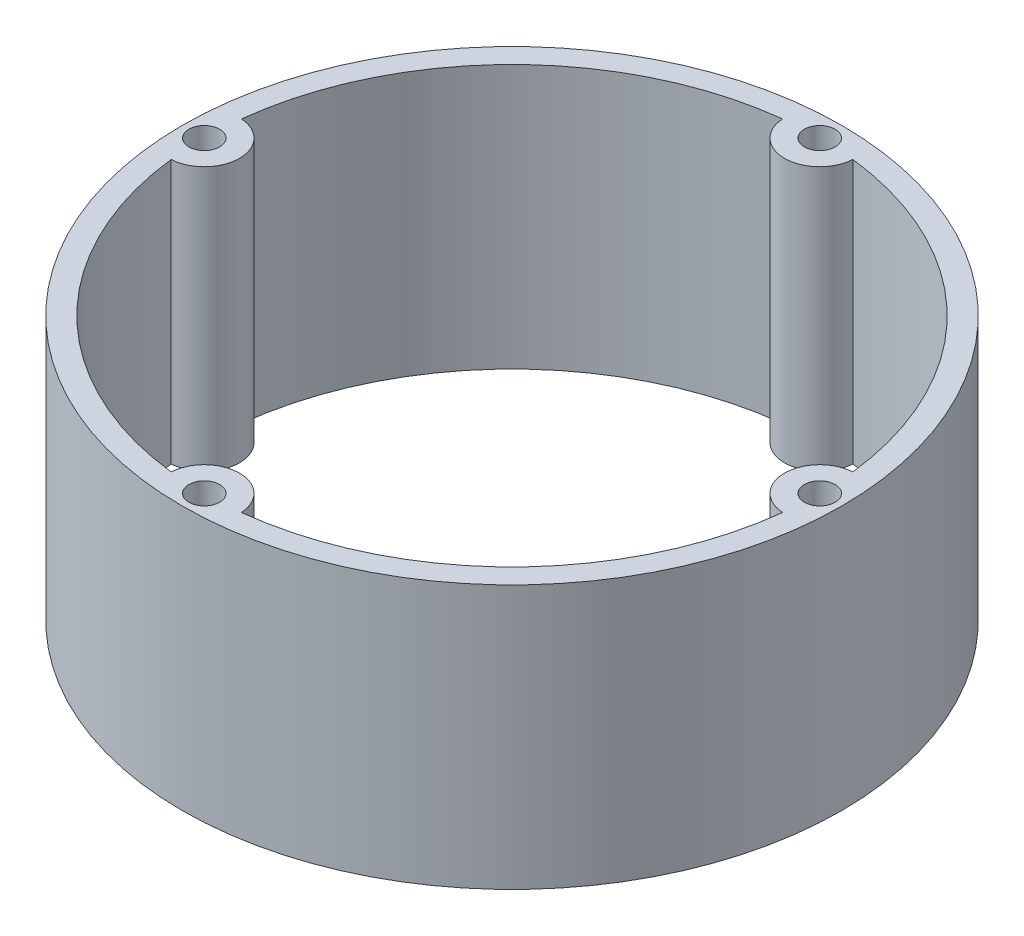
SolidWorks part; units mm, degrees
ref_plane "Ön Düzlem" through (0, 0, 0) normal (0, 0, 1) x (1, 0, 0)
ref_plane "Üst Düzlem" through (0, 0, 0) normal (0, 1, 0) x (1, 0, 0)
ref_plane "Sağ Düzlem" through (0, 0, 0) normal (1, 0, 0) x (0, 0, -1)
sketch "Çizim1" plane through (0, 0, 0) normal (0, 1, 0) x (1, 0, 0)
  circle A0 centre (0, 0) radius 37.5
  arc A13 (-34.7714, -3.9935) -> (-3.9935, -34.7714) centre (0, 0) ccw
  circle A14 centre (0, 35) radius 1.75
  circle A15 centre (35, 0) radius 1.75
  circle A16 centre (0, -35) radius 1.75
  circle A17 centre (-35, 0) radius 1.75
  arc A18 (-34.7714, -3.9935) -> (-34.7714, 3.9935) centre (-35, 0) ccw
  arc A19 (-3.9935, 34.7714) -> (3.9935, 34.7714) centre (0, 35) ccw
  arc A20 (34.7714, 3.9935) -> (34.7714, -3.9935) centre (35, 0) ccw
  arc A21 (3.9935, -34.7714) -> (-3.9935, -34.7714) centre (0, -35) ccw
  arc A22 (-3.9935, 34.7714) -> (-34.7714, 3.9935) centre (0, 0) ccw
  arc A23 (34.7714, 3.9935) -> (3.9935, 34.7714) centre (0, 0) ccw
  arc A24 (3.9935, -34.7714) -> (34.7714, -3.9935) centre (0, 0) ccw
  dimension "D1" = 75
  dimension "D2" = 4
  dimension "D3" = 4
extrude "Yükseklik-Ekstrüzyon1" add sketch "Çizim1" along normal blind 30
